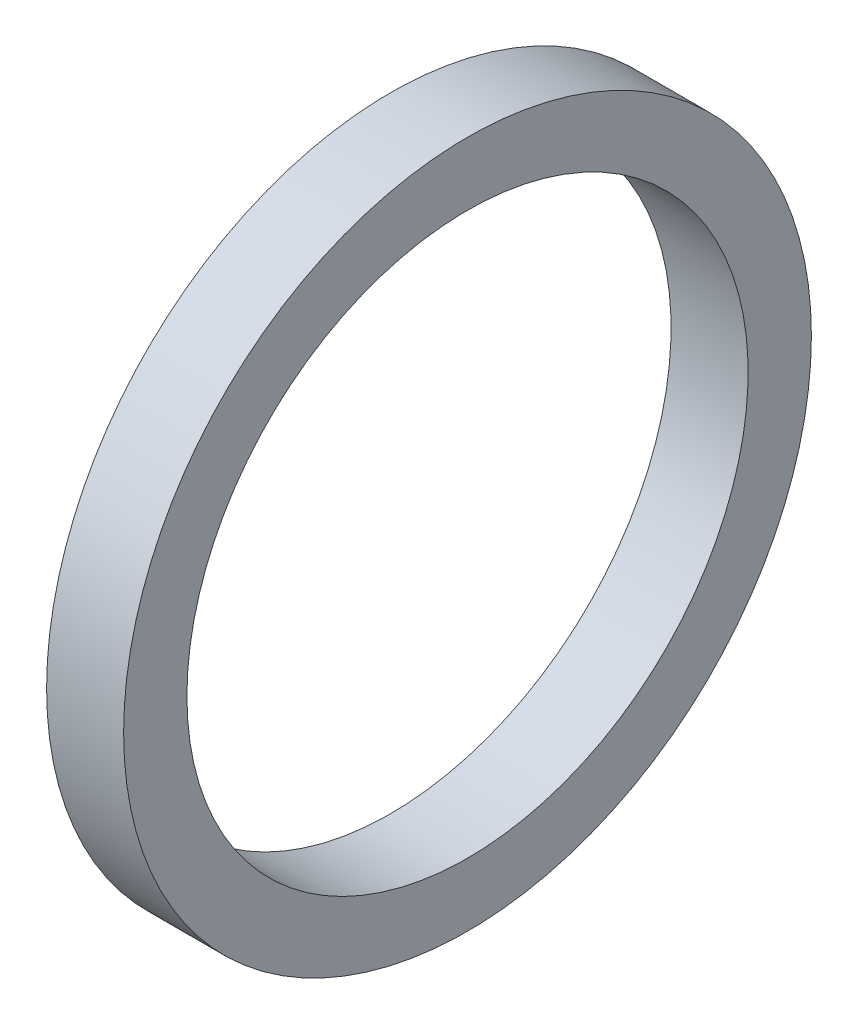
SolidWorks part; units mm, degrees
ref_plane "Plane1" through (0, 0, 0) normal (0, 0, 1) x (1, 0, 0)
ref_plane "Plane2" through (0, 0, 0) normal (0, 1, 0) x (1, 0, 0)
ref_plane "Plane3" through (0, 0, 0) normal (1, 0, 0) x (0, 0, -1)
sketch "Sketch1" plane through (0, 0, 0) normal (0, 0, 1) x (1, 0, 0)
  line L0 (-34.925, 0) -> (9.525, 0) construction
  line L1 (0, 51) -> (0, 62.5)
  line L2 (0, 62.5) -> (-14, 62.5)
  line L3 (-14, 62.5) -> (-14, 51)
  line L4 (-14, 51) -> (0, 51)
  dimension "Thickness" = 14
  dimension "Inside_dia" = 102
  dimension "Outside_dia" = 125
revolve "Base-Revolve" add sketch "Sketch1" angle 360 about L0
